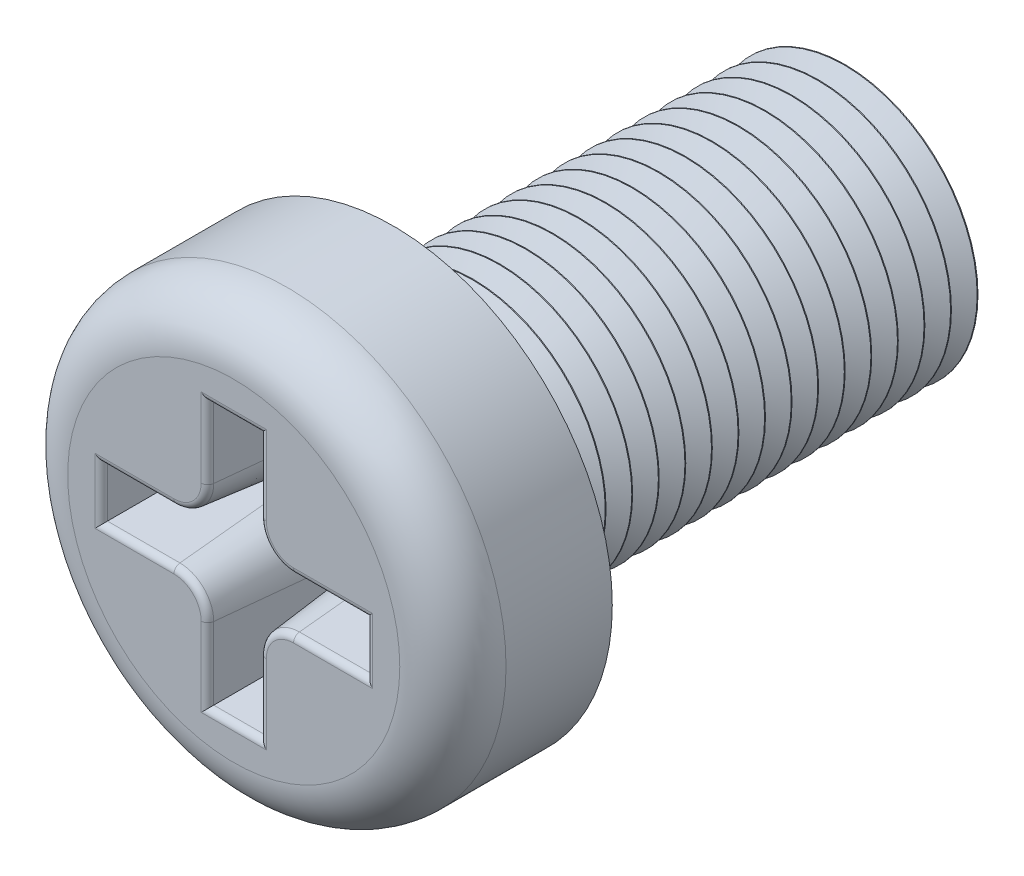
SolidWorks part; units mm, degrees
ref_plane "Front Plane" through (0, 0, 0) normal (0, 0, 1) x (1, 0, 0)
ref_plane "Top Plane" through (0, 0, 0) normal (0, 1, 0) x (1, 0, 0)
ref_plane "Right Plane" through (0, 0, 0) normal (1, 0, 0) x (0, 0, -1)
sketch "Sketch1" plane through (0, 0, 0) normal (0, 0, 1) x (1, 0, 0)
  circle A0 centre (0, 0) radius 3.3
  dimension "D1" = 6.6
extrude "Boss-Extrude1" add sketch "Sketch1" along normal blind 2.4
fillet "Fillet1" radius 0.8 1 edges at (3.3, 0, 2.4)
sketch "Sketch2" plane through (0, 0, 0) normal (0, 0, -1) x (-1, 0, 0)
  circle A0 centre (0, 0) radius 2
  dimension "D1" = 4
extrude "Boss-Extrude2" add sketch "Sketch2" along normal blind 7
sketch "Sketch4" plane through (0, 0, 2.4) normal (0, 0, 1) x (1, 0, 0)
  line L1 (-0.4, -2) -> (0.4, -2)
  line L2 (-0.4, -2) -> (-0.4, -0.9)
  line L3 (-0.4, 2) -> (0.4, 2)
  line L4 (0.4, -2) -> (0.4, -0.9)
  line L5 (-0.4, -2) -> (0.4, 2) construction
  line L6 (-0.4, 2) -> (0.4, -2) construction
  line L7 (-2, -0.4) -> (-0.9, -0.4)
  line L8 (-2, -0.4) -> (-2, 0.4)
  line L9 (-2, 0.4) -> (-0.9, 0.4)
  line L10 (2, -0.4) -> (2, 0.4)
  line L11 (-2, -0.4) -> (2, 0.4) construction
  line L12 (-2, 0.4) -> (2, -0.4) construction
  line L13 (-0.4, 0.9) -> (-0.4, 2)
  line L14 (0.9, -0.4) -> (2, -0.4)
  line L15 (0.4, 0.9) -> (0.4, 2)
  line L16 (0.9, 0.4) -> (2, 0.4)
  arc A0 (0.4, 0.9) -> (0.9, 0.4) centre (0.9, 0.9) ccw
  arc A1 (0.9, -0.4) -> (0.4, -0.9) centre (0.9, -0.9) ccw
  arc A2 (-0.4, -0.9) -> (-0.9, -0.4) centre (-0.9, -0.9) ccw
  arc A3 (-0.9, 0.4) -> (-0.4, 0.9) centre (-0.9, 0.9) ccw
  point P0 (0, 0)
  point P6 (0, 0)
  point P23 (-0.4, 0.4)
  dimension "D5" = 0.5
  dimension "D1" = 0.8
  dimension "D2" = 0.8
  dimension "D3" = 4
  dimension "D4" = 4
extrude "Cut-Extrude1" cut sketch "Sketch4" against normal blind 2 draft 6
fillet "Fillet2" radius 0.1 16 edges at (0, 2, 2.4) (-0.4, 1.45, 2.4) (-0.5464, 0.5464, 2.4) (-1.45, 0.4, 2.4) (-2, 0, 2.4) (-1.45, -0.4, 2.4) (-0.5464, -0.5464, 2.4) (-0.4, -1.45, 2.4) (0, -2, 2.4) (0.4, -1.45, 2.4) (0.5464, -0.5464, 2.4) (1.45, -0.4, 2.4) (2, 0, 2.4) (1.45, 0.4, 2.4) (0.5464, 0.5464, 2.4) (0.4, 1.45, 2.4)
sketch "Sketch5" plane through (0, 0, 0) normal (1, 0, 0) x (0, 0, -1)
  line L0 (7, 1.7) -> (7.2, 2.01)
  line L1 (7, -2) -> (7, 2) construction
  line L2 (7.2, 2.01) -> (6.8, 2.01)
  line L3 (6.8, 2.01) -> (7, 1.7)
  line L4 (7, 2) -> (0, 2) construction
  line L5 (0, 0) -> (12.2689, 0) construction
  dimension "D1" = 0.4
  dimension "D2" = 0.2
  dimension "D3" = 0.3
  dimension "D4" = 0.31
revolve "Cut-Revolve1" cut sketch "Sketch5" angle 360 about L5
sketch "Sketch6" plane through (0, 0, 0) normal (1, 0, 0) x (0, 0, -1)
  line L0 (8.2553, 0) -> (-3.6097, 0) construction
pattern_linear "LPattern1" count 17 spacing 0.4 along (0, 0, 1) of "Cut-Revolve1"
